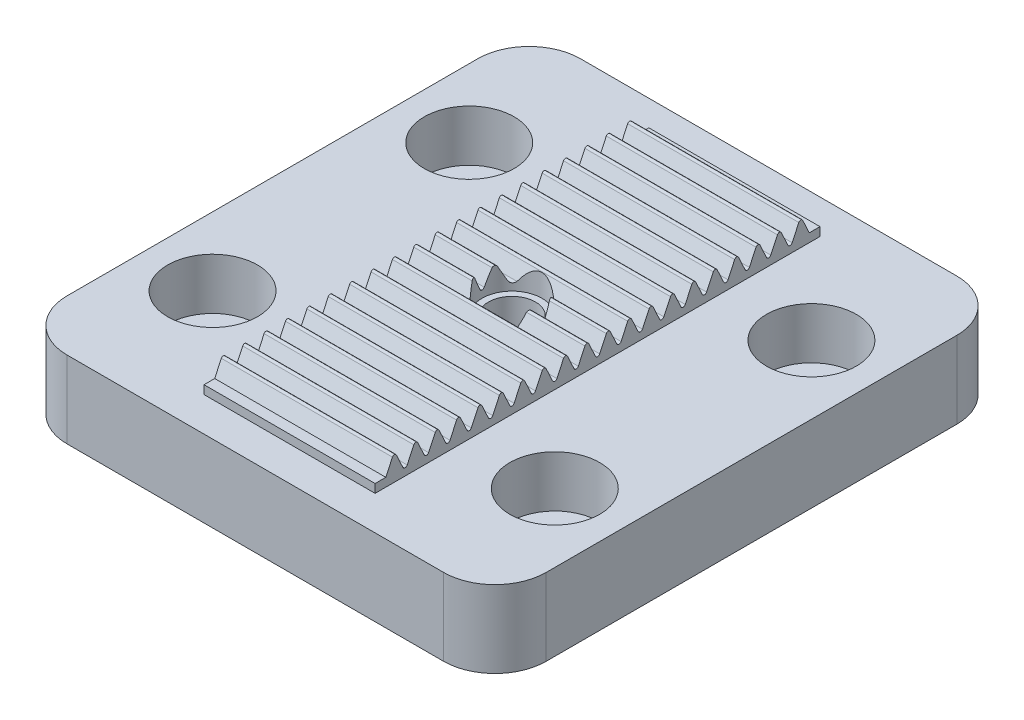
SolidWorks part; units mm, degrees
ref_plane "Front Plane" through (0, 0, 0) normal (0, 0, 1) x (1, 0, 0)
ref_plane "Top Plane" through (0, 0, 0) normal (0, 1, 0) x (1, 0, 0)
ref_plane "Right Plane" through (0, 0, 0) normal (1, 0, 0) x (0, 0, -1)
sketch "Sketch1" plane through (0, 0, 0) normal (0, 1, 0) x (1, 0, 0)
  line L1 (-28, -30) -> (28, -30)
  line L2 (-28, -30) -> (-28, 30)
  line L3 (-28, 30) -> (28, 30)
  line L4 (28, -30) -> (28, 30)
  line L5 (-28, -30) -> (28, 30) construction
  line L6 (-28, 30) -> (28, -30) construction
  line L7 (-20, -15) -> (20, -15) construction
  line L8 (-20, -15) -> (-20, 15) construction
  line L9 (-20, 15) -> (20, 15) construction
  line L10 (20, -15) -> (20, 15) construction
  line L11 (-20, -15) -> (20, 15) construction
  line L12 (-20, 15) -> (20, -15) construction
  circle A0 centre (-20, 15) radius 3.25
  circle A1 centre (-20, -15) radius 3.25
  circle A2 centre (20, -15) radius 3.25
  circle A3 centre (20, 15) radius 3 construction
  circle A4 centre (20, 15) radius 3.25
  point P0 (0, 0)
  point P6 (0, 0)
  dimension "D4" = 6
  dimension "D1" = 60
  dimension "D2" = 56
  dimension "D5" = 40
  dimension "D6" = 30
  dimension "D3" = 0.25
extrude "Boss-Extrude1" add sketch "Sketch1" along normal blind 3
sketch "Sketch2" plane through (0, 3, 0) normal (0, 1, 0) x (1, 0, 0)
  line L4 (28, -30) -> (28, 30)
  line L5 (28, 30) -> (-28, 30)
  line L6 (-28, 30) -> (-28, -30)
  line L7 (-28, -30) -> (28, -30)
  line L8 (28, -30) -> (28, 30)
  line L9 (28, 30) -> (-28, 30)
  line L10 (-28, 30) -> (-28, -30)
  line L11 (-28, -30) -> (28, -30)
  circle A0 centre (-20, 15) radius 5.25
  circle A1 centre (-20, -15) radius 5.25
  circle A2 centre (20, -15) radius 5.25
  circle A3 centre (20, 15) radius 5 construction
  circle A4 centre (20, 15) radius 5.25
  dimension "D3" = 10
  dimension "D2" = 0.25
extrude "Boss-Extrude2" add sketch "Sketch2" along normal blind 6
fillet "Fillet1" radius 6 4 edges at (28, 4.5, -30) (-28, 4.5, -30) (-28, 4.5, 30) (28, 4.5, 30)
sketch "Sketch3" plane through (0, 0, 0) normal (1, 0, 0) x (0, 0, -1)
  line L0 (-26, 9) -> (-26, 10)
  line L1 (-26, 10) -> (-24.75, 10)
  line L3 (24.75, 10) -> (26, 10)
  line L4 (26, 10) -> (26, 9)
  line L5 (26, 9) -> (-26, 9)
  line L6 (-26, 9) -> (-30, 9) construction
  line L7 (26, 9) -> (30, 9) construction
  line L8 (-24.75, 10) -> (-23.9766, 11.6586)
  line L9 (-23.5234, 11.6586) -> (-22.75, 10)
  line L10 (-23.75, 12.1445) -> (-23.75, 10) construction
  line L13 (-24.75, 10) -> (-22.75, 10) construction
  line L14 (-22.75, 10) -> (-22.25, 10) construction
  line L15 (-22.25, 10) -> (-21.4766, 11.6586)
  line L16 (-21.0234, 11.6586) -> (-20.25, 10)
  line L17 (-19.75, 10) -> (-18.9766, 11.6586)
  line L18 (-18.5234, 11.6586) -> (-17.75, 10)
  line L19 (-17.25, 10) -> (-16.4766, 11.6586)
  line L20 (-16.0234, 11.6586) -> (-15.25, 10)
  line L21 (-14.75, 10) -> (-13.9766, 11.6586)
  line L22 (-13.5234, 11.6586) -> (-12.75, 10)
  line L23 (-12.25, 10) -> (-11.4766, 11.6586)
  line L24 (-11.0234, 11.6586) -> (-10.25, 10)
  line L25 (-9.75, 10) -> (-8.9766, 11.6586)
  line L26 (-8.5234, 11.6586) -> (-7.75, 10)
  line L27 (-7.25, 10) -> (-6.4766, 11.6586)
  line L28 (-6.0234, 11.6586) -> (-5.25, 10)
  line L29 (-4.75, 10) -> (-3.9766, 11.6586)
  line L30 (-3.5234, 11.6586) -> (-2.75, 10)
  line L31 (-2.25, 10) -> (-1.4766, 11.6586)
  line L32 (-1.0234, 11.6586) -> (-0.25, 10)
  line L33 (0.25, 10) -> (1.0234, 11.6586)
  line L34 (1.4766, 11.6586) -> (2.25, 10)
  line L35 (2.75, 10) -> (3.5234, 11.6586)
  line L36 (3.9766, 11.6586) -> (4.75, 10)
  line L37 (5.25, 10) -> (6.0234, 11.6586)
  line L38 (6.4766, 11.6586) -> (7.25, 10)
  line L39 (7.75, 10) -> (8.5234, 11.6586)
  line L40 (8.9766, 11.6586) -> (9.75, 10)
  line L41 (10.25, 10) -> (11.0234, 11.6586)
  line L42 (11.4766, 11.6586) -> (12.25, 10)
  line L43 (12.75, 10) -> (13.5234, 11.6586)
  line L44 (13.9766, 11.6586) -> (14.75, 10)
  line L45 (15.25, 10) -> (16.0234, 11.6586)
  line L46 (16.4766, 11.6586) -> (17.25, 10)
  line L47 (17.75, 10) -> (18.5234, 11.6586)
  line L48 (18.9766, 11.6586) -> (19.75, 10)
  line L49 (20.25, 10) -> (21.0234, 11.6586)
  line L50 (21.4766, 11.6586) -> (22.25, 10)
  line L51 (22.75, 10) -> (23.5234, 11.6586)
  line L52 (23.9766, 11.6586) -> (24.75, 10)
  arc A0 (-23.9766, 11.6586) -> (-23.5234, 11.6586) centre (-23.75, 11.553) cw
  arc A1 (-22.75, 10) -> (-22.25, 10) centre (-22.5, 10.1166) ccw
  arc A2 (-21.4766, 11.6586) -> (-21.0234, 11.6586) centre (-21.25, 11.553) cw
  arc A3 (-20.25, 10) -> (-19.75, 10) centre (-20, 10.1166) ccw
  arc A4 (-18.9766, 11.6586) -> (-18.5234, 11.6586) centre (-18.75, 11.553) cw
  arc A5 (-17.75, 10) -> (-17.25, 10) centre (-17.5, 10.1166) ccw
  arc A6 (-16.4766, 11.6586) -> (-16.0234, 11.6586) centre (-16.25, 11.553) cw
  arc A7 (-15.25, 10) -> (-14.75, 10) centre (-15, 10.1166) ccw
  arc A8 (-13.9766, 11.6586) -> (-13.5234, 11.6586) centre (-13.75, 11.553) cw
  arc A9 (-12.75, 10) -> (-12.25, 10) centre (-12.5, 10.1166) ccw
  arc A10 (-11.4766, 11.6586) -> (-11.0234, 11.6586) centre (-11.25, 11.553) cw
  arc A11 (-10.25, 10) -> (-9.75, 10) centre (-10, 10.1166) ccw
  arc A12 (-8.9766, 11.6586) -> (-8.5234, 11.6586) centre (-8.75, 11.553) cw
  arc A13 (-7.75, 10) -> (-7.25, 10) centre (-7.5, 10.1166) ccw
  arc A14 (-6.4766, 11.6586) -> (-6.0234, 11.6586) centre (-6.25, 11.553) cw
  arc A15 (-5.25, 10) -> (-4.75, 10) centre (-5, 10.1166) ccw
  arc A16 (-3.9766, 11.6586) -> (-3.5234, 11.6586) centre (-3.75, 11.553) cw
  arc A17 (-2.75, 10) -> (-2.25, 10) centre (-2.5, 10.1166) ccw
  arc A18 (-1.4766, 11.6586) -> (-1.0234, 11.6586) centre (-1.25, 11.553) cw
  arc A19 (-0.25, 10) -> (0.25, 10) centre (0, 10.1166) ccw
  arc A20 (1.0234, 11.6586) -> (1.4766, 11.6586) centre (1.25, 11.553) cw
  arc A21 (2.25, 10) -> (2.75, 10) centre (2.5, 10.1166) ccw
  arc A22 (3.5234, 11.6586) -> (3.9766, 11.6586) centre (3.75, 11.553) cw
  arc A23 (4.75, 10) -> (5.25, 10) centre (5, 10.1166) ccw
  arc A24 (6.0234, 11.6586) -> (6.4766, 11.6586) centre (6.25, 11.553) cw
  arc A25 (7.25, 10) -> (7.75, 10) centre (7.5, 10.1166) ccw
  arc A26 (8.5234, 11.6586) -> (8.9766, 11.6586) centre (8.75, 11.553) cw
  arc A27 (9.75, 10) -> (10.25, 10) centre (10, 10.1166) ccw
  arc A28 (11.0234, 11.6586) -> (11.4766, 11.6586) centre (11.25, 11.553) cw
  arc A29 (12.25, 10) -> (12.75, 10) centre (12.5, 10.1166) ccw
  arc A30 (13.5234, 11.6586) -> (13.9766, 11.6586) centre (13.75, 11.553) cw
  arc A31 (14.75, 10) -> (15.25, 10) centre (15, 10.1166) ccw
  arc A32 (16.0234, 11.6586) -> (16.4766, 11.6586) centre (16.25, 11.553) cw
  arc A33 (17.25, 10) -> (17.75, 10) centre (17.5, 10.1166) ccw
  arc A34 (18.5234, 11.6586) -> (18.9766, 11.6586) centre (18.75, 11.553) cw
  arc A35 (19.75, 10) -> (20.25, 10) centre (20, 10.1166) ccw
  arc A36 (21.0234, 11.6586) -> (21.4766, 11.6586) centre (21.25, 11.553) cw
  arc A37 (22.25, 10) -> (22.75, 10) centre (22.5, 10.1166) ccw
  arc A38 (23.5234, 11.6586) -> (23.9766, 11.6586) centre (23.75, 11.553) cw
  arc A40 (24.75, 10) -> (25.25, 10) centre (25, 10.1166) ccw [skipped]
  point P15 (-23.75, 10)
  dimension "D4" = 0.25
  dimension "D1" = 4
  dimension "D2" = 50
  dimension "D3" = 2
  dimension "D5" = 1
  dimension "D7" = 0.5
  dimension "D8" = 20
extrude "Boss-Extrude3" add sketch "Sketch3" along normal mid plane 20
sketch "Sketch4" plane through (0, 0, 0) normal (0, 1, 0) x (1, 0, 0)
  line L0 (-28, 30) -> (28, -30) construction
  circle A0 centre (0, 0) radius 2.5 construction
  circle A1 centre (0, 0) radius 2.75
  dimension "D2" = 5
  dimension "D1" = 0.25
extrude "Cut-Extrude2" cut sketch "Sketch4" along normal through all
sketch "Sketch5" plane through (0, 9, 0) normal (0, 1, 0) x (1, 0, 0)
  circle A0 centre (0, 0) radius 3.5
  dimension "D1" = 7
extrude "Cut-Extrude3" cut sketch "Sketch5" along normal through all
sketch "Sketch6" plane through (0, 0, 0) normal (0, -1, 0) x (1, 0, 0)
  line L0 (-20, -15) -> (20, 15) construction
  line L1 (0, 4.6188) -> (-4, 2.3094) construction
  line L2 (-4, 2.3094) -> (-4, -2.3094) construction
  line L3 (-4, -2.3094) -> (0, -4.6188) construction
  line L4 (0, -4.6188) -> (4, -2.3094) construction
  line L5 (4, -2.3094) -> (4, 2.3094) construction
  line L6 (4, 2.3094) -> (0, 4.6188) construction
  line L7 (4.25, -2.4537) -> (4.25, 2.4537)
  line L8 (4.25, 2.4537) -> (0, 4.9075)
  line L9 (0, 4.9075) -> (-4.25, 2.4537)
  line L10 (-4.25, 2.4537) -> (-4.25, -2.4537)
  line L11 (-4.25, -2.4537) -> (0, -4.9075)
  line L12 (0, -4.9075) -> (4.25, -2.4537)
  circle A0 centre (0, 0) radius 4 construction
  dimension "D1" = 0.25
  dimension "D2" = 8
extrude "Cut-Extrude4" cut sketch "Sketch6" against normal blind 5
equation "\"Tolerance\" = 0.25mm"
equation "\"Pocket_Head_M5\"= 8mm"
equation "\"Pocket_Head_M4\" = 7mm"
equation "\"Pocket_Nut_M4\" = 7mm"
equation "\"Pocket_Nut_M2.5\" = 5mm"
equation "\"Pocket_Nut_M5\"= 8mm"
equation "\"Pocket_Nut_M3\"= 5.5mm"
equation "\"Pocket_Head_M3\"= 5.5mm"
equation "\"Pocket_Head_M2.5\" = 4.7mm"
equation "\"D3@Sketch1\"=\"Tolerance\""
equation "\"D2@Sketch2\"=\"Tolerance\""
equation "\"Pocket_Head_M6\" = 10mm"
equation "\"D3@Sketch2\"=\"Pocket_Head_M6\""
equation "\"D1@Sketch4\"=\"Tolerance\""
equation "\"D1@Sketch6\"=\"Tolerance\""
equation "\"D2@Sketch6\"=\"Pocket_Nut_M5\""
